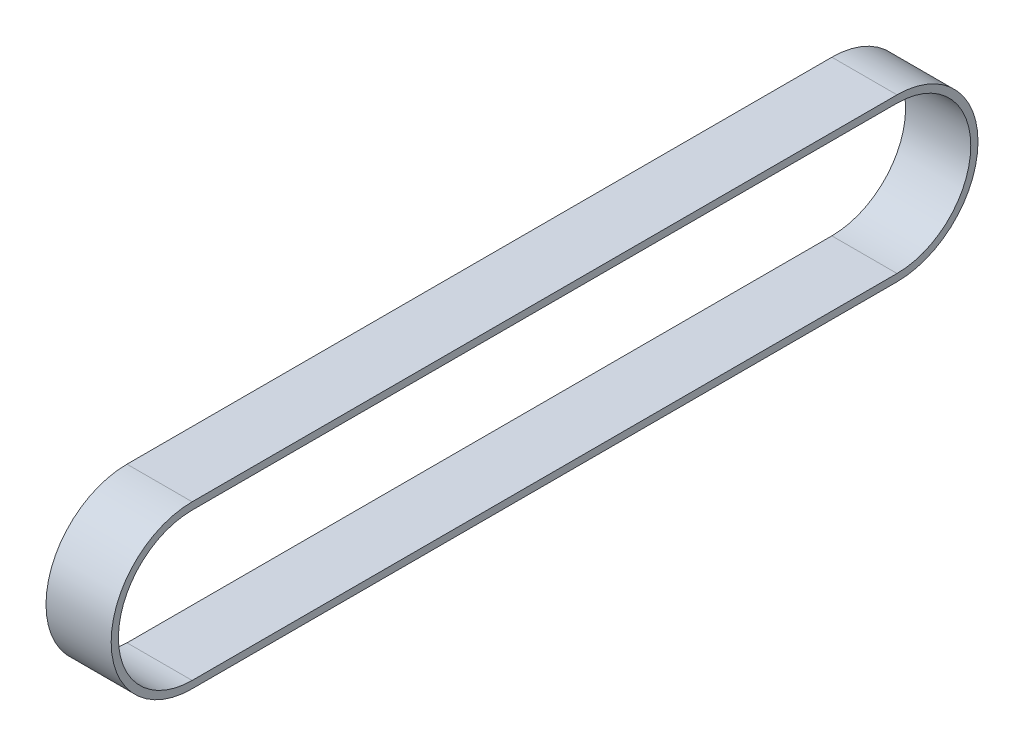
SolidWorks part; units mm, degrees
material "Rubber"
ref_plane "Frente" through (0, 0, 0) normal (0, 0, 1) x (1, 0, 0)
ref_plane "Topo" through (0, 0, 0) normal (0, 1, 0) x (1, 0, 0)
ref_plane "Lateral" through (0, 0, 0) normal (1, 0, 0) x (0, 0, -1)
sketch "Sketch1" plane through (0, 0, 0) normal (1, 0, 0) x (0, 0, -1)
  line L0 (-97.3613, 10.185) -> (0, 10.185)
  line L1 (0, 10.185) -> (0, -10.185) construction
  line L2 (0, -10.185) -> (-97.3613, -10.185)
  line L3 (-97.3613, -10.185) -> (-97.3613, 10.185) construction
  arc A0 (0, -10.185) -> (0, 10.185) centre (0, 0) ccw
  arc A1 (-97.3613, 10.185) -> (-97.3613, -10.185) centre (-97.3613, 0) ccw
  dimension "D1" = 10.185
  dimension "D2" = 31.9971
  dimension "D3" = 97.3613
extrude "Extrude-Thin1" add sketch "Sketch1" along normal mid plane 9 thin thin type one direction wall 1
